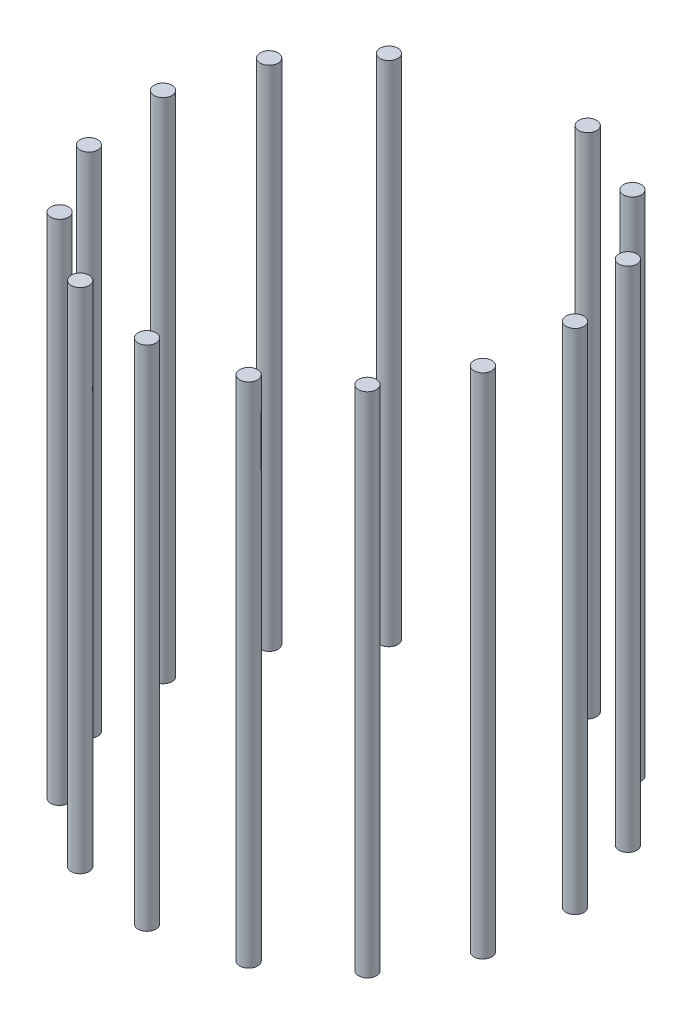
SolidWorks part; units mm, degrees
ref_plane "Front Plane" through (0, 0, 0) normal (0, 0, 1) x (1, 0, 0)
ref_plane "Top Plane" through (0, 0, 0) normal (0, 1, 0) x (1, 0, 0)
ref_plane "Right Plane" through (0, 0, 0) normal (1, 0, 0) x (0, 0, -1)
sketch "Sketch1" plane through (0, 0, 0) normal (0, 1, 0) x (1, 0, 0)
  line L0 (14.2081, -1.6197) -> (12.873, 4.2298) construction
  line L1 (12.873, 4.2298) -> (12.428, 6.1797) construction
  circle A0 centre (15.7542, 6.2295) radius 0.35
  circle A1 centre (18.8131, 4.922) radius 0.35
  circle A2 centre (21.0757, 2.4835) radius 0.35
  circle A3 centre (22.1509, -0.6646) radius 0.35
  circle A4 centre (21.8527, -3.9778) radius 0.35
  circle A5 centre (20.2327, -6.8832) radius 0.35
  circle A6 centre (17.571, -8.8786) radius 0.35
  circle A7 centre (14.3278, -9.6188) radius 0.35
  circle A8 centre (11.0639, -8.9759) radius 0.35
  circle A9 centre (8.3437, -7.0611) radius 0.35
  circle A10 centre (6.6375, -4.2054) radius 0.35
  circle A11 centre (6.2403, -0.9026) radius 0.35
  circle A12 centre (7.2209, 2.2762) radius 0.35
  circle A13 centre (9.4095, 4.7813) radius 0.35
extrude "Boss-Extrude1" add sketch "Sketch1" along normal blind 19.9
